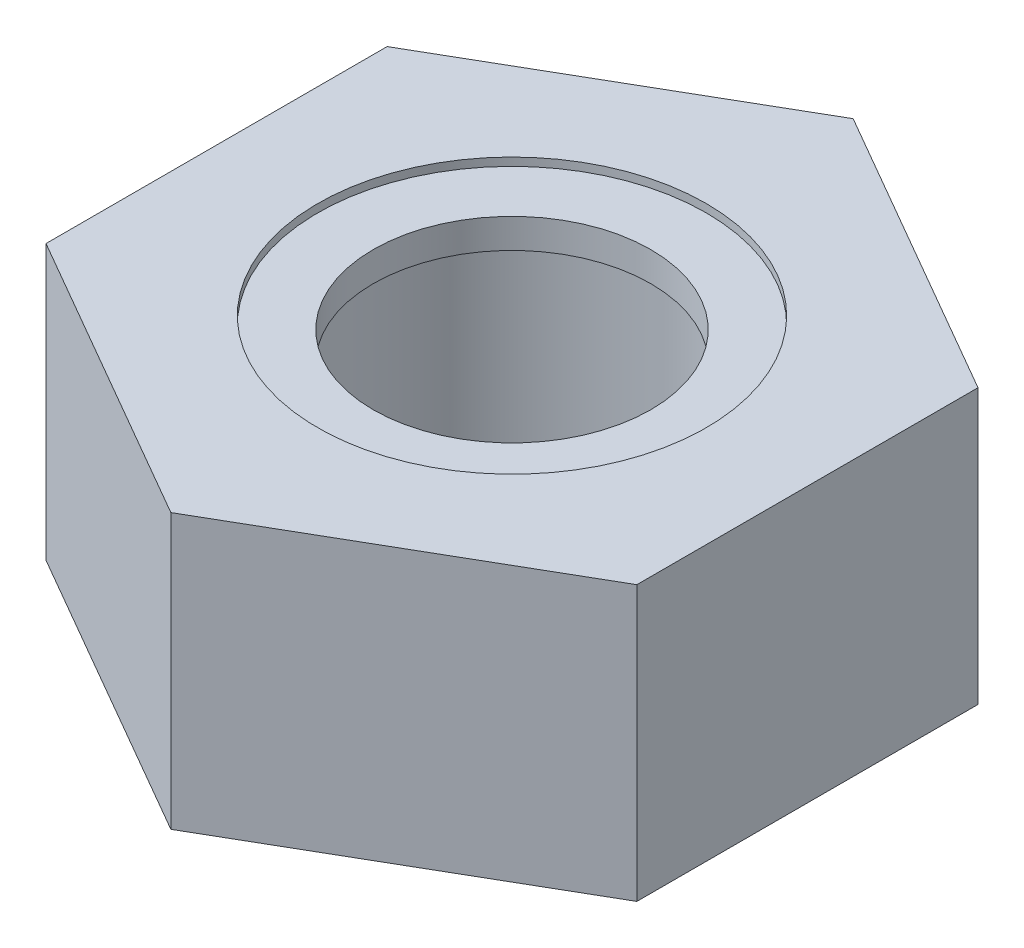
SolidWorks part; units mm, degrees
material "Stainless Steel (ferritic)"
ref_plane "Front" through (0, 0, 0) normal (0, 0, 1) x (1, 0, 0)
ref_plane "Top" through (0, 0, 0) normal (0, 1, 0) x (1, 0, 0)
ref_plane "Right" through (0, 0, 0) normal (1, 0, 0) x (0, 0, -1)
sketch "Sketch1" plane through (0, 0, 0) normal (0, 1, 0) x (1, 0, 0)
  line L1 (0, 6.4158) -> (-5.5563, 3.2079)
  line L2 (-5.5563, 3.2079) -> (-5.5562, -3.2079)
  line L3 (-5.5562, -3.2079) -> (0, -6.4158)
  line L4 (0, -6.4158) -> (5.5562, -3.2079)
  line L5 (5.5562, -3.2079) -> (5.5562, 3.2079)
  line L6 (5.5562, 3.2079) -> (0, 6.4158)
  circle A0 centre (0, 0) radius 5.5562 construction
  dimension "Hex Flats" = 11.1125
extrude "Extrude1" add sketch "Sketch1" along normal blind 5.1594
sketch "Sketch2" plane through (0, 0, 0) normal (1, 0, 0) x (0, 0, -1)
  line L0 (-3.175, 0) -> (-3.175, 5.1594) construction
  line L1 (0, 0) -> (3.175, 0)
  line L2 (0, 0) -> (0, 5.1594)
  line L3 (0, 5.1594) -> (3.175, 5.1594)
  line L4 (3.175, 0) -> (3.175, 5.1594)
  line L5 (-3.2079, 5.1594) -> (3.2079, 5.1594) construction
  line L7 (0, -3.175) -> (0, 0) construction
  dimension "Thread Dia" = 6.35
revolve "Revolve1" add sketch "Sketch2" angle 360 about L7
sketch "Sketch3" plane through (0, 0, 0) normal (1, 0, 0) x (0, 0, -1)
  line L0 (3.175, 5.1594) -> (-3.175, 5.1594) construction
  line L1 (-3.175, 5.1594) -> (-3.175, 3.8894) construction
  line L2 (-3.175, 3.8894) -> (3.175, 5.1594) construction
  line L3 (3.175, 5.1594) -> (3.2061, 5.0037) construction
  line L4 (3.2061, 5.0037) -> (3.4241, 3.914)
  line L5 (3.4241, 3.914) -> (2.6722, 4.1684)
  line L6 (2.6722, 4.1684) -> (2.6099, 4.4797)
  line L7 (2.6099, 4.4797) -> (3.2061, 5.0037)
  line L8 (2.641, 4.3241) -> (3.3151, 4.4589) construction
  line L9 (3.175, 5.1594) -> (3.175, 4.4309) construction
  line L10 (3.175, 4.4309) -> (-3.175, 3.1609) construction
  line L11 (-3.175, 3.1609) -> (-3.175, 3.8894) construction
  line L12 (-0.2727, 5.1594) -> (0.2727, 2.4323) construction
  line L13 (-3.175, 0) -> (-3.175, 5.1594) construction
  line L14 (0, 5.1594) -> (3.175, 5.1594) construction
  line L15 (3.175, 0) -> (3.175, 5.1594) construction
  point P13 (0, 3.7959)
  dimension "D1" = 0.1588
  dimension "D2" = 0.3175
  dimension "Thread Pitch" = 1.27
  dimension "D4" = 60
  dimension "D5" = 1.27
sketch "Sketch4" plane through (0, 0, 0) normal (1, 0, 0) x (0, 0, -1)
  line L0 (0, 5.1594) -> (3.175, 5.1594)
  line L1 (3.175, 5.1594) -> (2.6099, 4.8959)
  line L2 (2.6099, 4.8959) -> (2.6099, 0.2635)
  line L3 (2.6099, 0.2635) -> (3.175, 0)
  line L4 (3.175, 0) -> (0, 0)
  line L5 (0, 0) -> (0, 5.1594)
  line L6 (3.175, 0) -> (3.175, 5.1594) construction
  line L7 (0, 5.1594) -> (3.175, 5.1594) construction
  line L8 (0, 0) -> (3.175, 0) construction
  line L9 (0, 0) -> (0, 5.1594) construction
  line L10 (0, 5.1594) -> (0, 5.7829) construction
  dimension "D1" = 25
revolve "Cut-Revolve2" cut sketch "Sketch4" angle 360 about L10
combine bodies "Combine1" operation type subtract main body 112 bodies to subtract 109
sketch "Sketch5" plane through (0, 0, 0) normal (1, 0, 0) x (0, 0, -1)
  line L0 (0, 0) -> (5.5562, 0)
  line L1 (5.5562, 0) -> (6.4158, 0.4008)
  line L2 (6.4158, 0.4008) -> (6.4158, 3.8987)
  line L3 (6.4158, 3.8987) -> (5.5562, 4.2995)
  line L4 (4.6964, 5.1594) -> (4.6964, 6.4294)
  line L5 (4.6964, 6.4294) -> (7.6858, 6.4294)
  line L6 (7.6858, 6.4294) -> (7.6858, -1.27)
  line L7 (7.6858, -1.27) -> (0, -1.27)
  line L8 (0, -1.27) -> (0, 0)
  line L9 (5.5562, 4.2995) -> (5.5562, 0) construction
  line L10 (0, 0) -> (3.175, 0) construction
  line L13 (6.4158, 2.1497) -> (7.6858, 2.1497) construction
  line L14 (6.4158, 5.1594) -> (6.4158, 0) construction
  line L15 (0, 0) -> (0, 6.4294) construction
  line L20 (0, 6.4294) -> (4.6964, 6.4294) construction
  line L22 (0, 5.1594) -> (3.175, 5.1594) construction
  arc A0 (5.5562, 4.2995) -> (4.6964, 5.1594) centre (4.6964, 4.2995) ccw
  dimension "D1" = 25
  dimension "D2" = 1.27
  dimension "D3" = 5.1594
  dimension "D4" = 0.8599
sketch "Sketch6" plane through (0, 0, 0) normal (1, 0, 0) x (0, 0, -1)
  line L0 (0, 4.2995) -> (5.4038, 4.2995)
  line L1 (4.6964, 5.007) -> (3.6531, 5.007)
  line L2 (0, 6.4294) -> (0, 4.2995)
  line L3 (3.6531, 6.4294) -> (0, 6.4294)
  line L4 (0, 6.4294) -> (4.6964, 6.4294) construction
  line L5 (0, 0) -> (0, 6.4294) construction
  line L6 (0, 6.4294) -> (0, 44.323) construction
  line L7 (3.6531, 5.007) -> (3.6531, 6.4294)
  line L8 (4.6964, 5.1594) -> (4.6964, 5.007) construction
  line L9 (3.6531, 5.007) -> (2.6099, 5.007) construction
  line L10 (2.6099, 5.007) -> (2.6099, 4.8959) construction
  arc A0 (5.4038, 4.2995) -> (4.6964, 5.007) centre (4.6964, 4.2995) ccw
  arc A1 (5.5562, 4.2995) -> (4.6964, 5.1594) centre (4.6964, 4.2995) ccw construction
  dimension "D1" = 0.1524
revolve "Cut-Revolve4" cut sketch "Sketch6" angle 360 about L6
sketch "Sketch7" plane through (0, 0, 0) normal (1, 0, 0) x (0, 0, -1)
  line L0 (2.6099, 4.3757) -> (5.323, 4.3757)
  line L1 (4.6964, 4.9308) -> (2.6099, 4.9308)
  line L2 (2.6099, 4.9308) -> (2.6099, 4.3757)
  line L3 (2.6099, 4.3757) -> (0, 4.3757) construction
  line L4 (0, 4.3757) -> (0, 4.9308) construction
  line L5 (0, 4.9308) -> (2.6099, 4.9308) construction
  line L6 (2.6099, 4.3757) -> (2.6099, 4.2995) construction
  line L7 (0, 4.2995) -> (5.4038, 4.2995) construction
  line L8 (4.6964, 4.9308) -> (4.6964, 5.007) construction
  arc A0 (5.323, 4.3757) -> (4.6964, 4.9308) centre (4.6964, 4.2995) ccw
  arc A2 (5.4038, 4.2995) -> (4.6964, 5.007) centre (4.6964, 4.2995) ccw construction
  dimension "D1" = 0.0762
revolve "Revolve2" add sketch "Sketch7" angle 360 about L4
equation "\"D1@Sketch3\"=\"Thread Pitch@Sketch3\"/8"
equation "\"D2@Sketch3\"=\"Thread Pitch@Sketch3\"/4"
equation "\"D5@Sketch3\"=\"Thread Pitch@Sketch3\""
equation "\"D4@Sketch5\"=\"Height@Extrude1\"/6"
